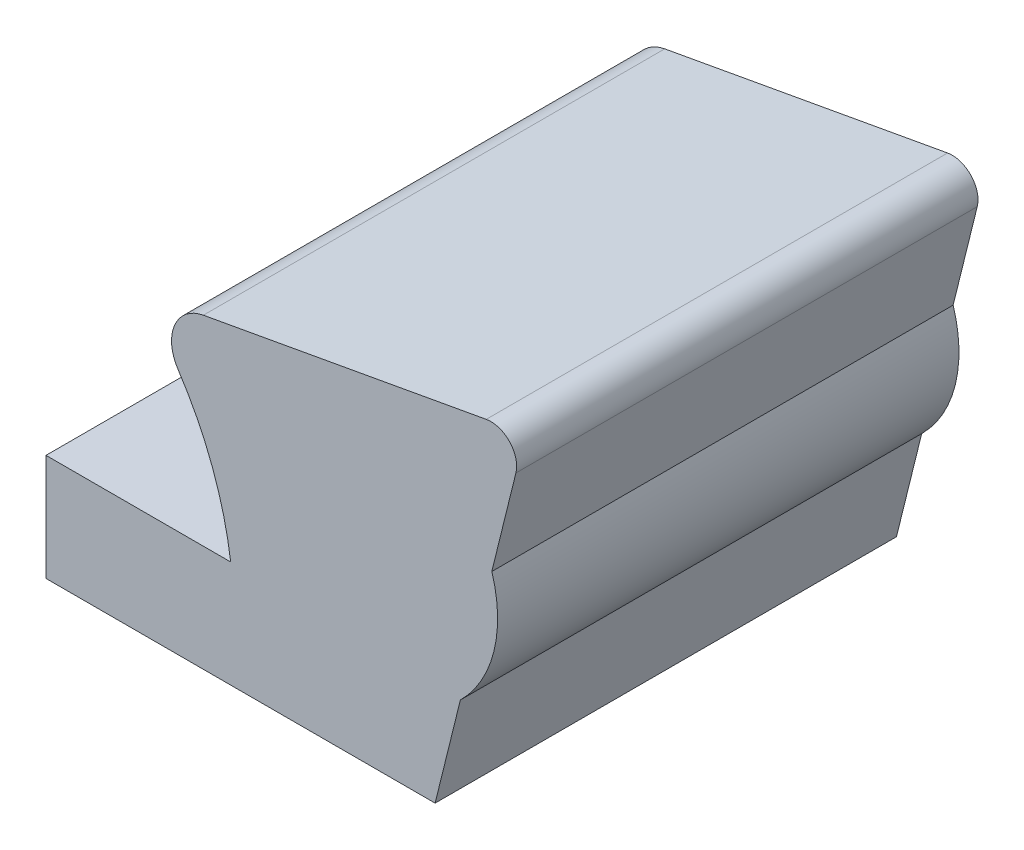
SolidWorks part; units mm, degrees
ref_plane "前视基准面" through (0, 0, 0) normal (0, 0, 1) x (1, 0, 0)
ref_plane "上视基准面" through (0, 0, 0) normal (0, 1, 0) x (1, 0, 0)
ref_plane "右视基准面" through (0, 0, 0) normal (1, 0, 0) x (0, 0, -1)
sketch "草图2" plane through (0, 0, 0) normal (0, 0, 1) x (1, 0, 0)
  line L0 (136.6039, 62.5138) -> (154.1159, 133.246)
  line L1 (52.2591, 37.348) -> (26.1206, 28.5308)
  line L2 (147.682, 140.1021) -> (86.3738, 128.9979)
  line L3 (0, 28.5308) -> (0, 0)
  line L5 (0, 0) -> (140.98, 0)
  line L6 (26.1206, 28.5308) -> (0, 28.5308)
  line L7 (87.78, 14.3923) -> (87.78, 0) construction
  line L11 (122.9685, 103.95) -> (148.68, 134.5918) construction
  line L12 (131.9282, 26.834) -> (115.25, 26.834)
  line L13 (120.3818, 62.5138) -> (136.6039, 62.5138)
  line L14 (115.25, 26.834) -> (120.3818, 62.5138)
  line L15 (52.2591, 85.6315) -> (92.2882, 85.6315)
  line L18 (52.2591, 85.6315) -> (52.2591, 37.348)
  line L21 (140.98, 0) -> (131.9282, 26.834)
  line L23 (87.8709, 120.7324) -> (122.9685, 103.95) construction
  arc A3 (86.3738, 128.9979) -> (80.8637, 116.1) centre (87.8709, 120.7324) ccw
  circle A8 centre (122.9685, 103.95) radius 27.1849
  arc A11 (92.2882, 85.6315) -> (80.8637, 116.1) centre (20.1345, 75.9527) ccw
  arc A12 (154.1159, 133.246) -> (147.682, 140.1021) centre (148.68, 134.5918) ccw
  point P0 (404.8134, 69.7647)
  point P1 (70.49, 0)
  dimension "D1" = 54.3698
  dimension "D2" = 8.4
  dimension "D3" = 72.8
  dimension "D4" = 5.6
  dimension "D5" = 20.1345
  dimension "D6" = 26.1206
  dimension "D7" = 52.2591
  dimension "D8" = 80.8637
  dimension "D9" = 87.78
  dimension "D10" = 40
  dimension "D11" = 148.68
  dimension "D12" = 92.2882
  dimension "D13" = 115.25
  dimension "D14" = 120.3818
  dimension "D16" = 131.9282
  dimension "D17" = 136.6039
  dimension "D18" = 140.98
  dimension "D19" = 26.834
  dimension "D20" = 28.5308
  dimension "D21" = 154.1159
  dimension "D22" = 85.6315
  dimension "D23" = 50
  dimension "D26" = 103.95
extrude "凸台-拉伸1" add sketch "草图2" along normal mid plane 100 contours A11 L15 L18 L1 L6 L3 L5 L21 L12 L14 L13 L0 A8 L2 A3 | L0 A8 L2 | L2 A8 | L0 A12 L2 A8
sketch "草图3" plane through (0, 0, 50) normal (0, 0, 1) x (1, 0, 0)
  line L0 (120.3818, 62.5138) -> (52.2591, 62.5138)
  line L1 (52.2591, 85.6315) -> (52.2591, 37.348) construction
split "分割1" trim tools "草图3" bodies to split 106 resulting bodies 107 108
delete or keep bodies "实体-删除/保留 1" type keep bodies bodies 107
